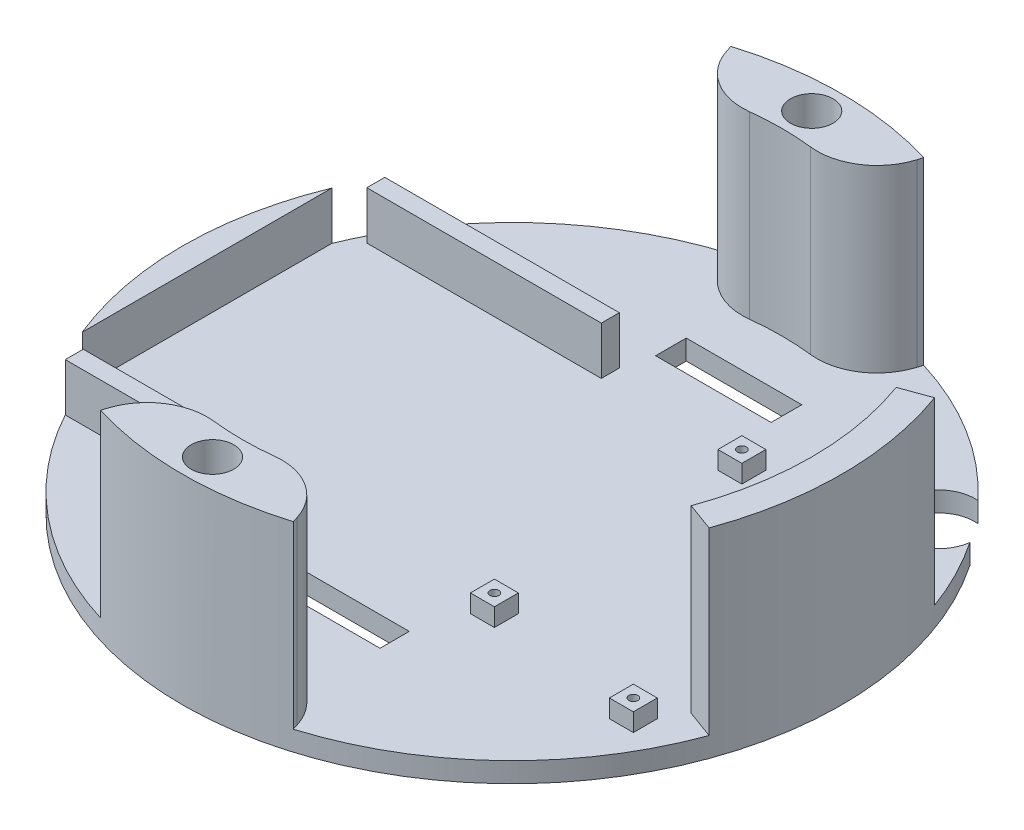
SolidWorks part; units mm, degrees
ref_plane "Front Plane" through (0, 0, 0) normal (0, 0, 1) x (1, 0, 0)
ref_plane "Top Plane" through (0, 0, 0) normal (0, 1, 0) x (1, 0, 0)
ref_plane "Right Plane" through (0, 0, 0) normal (1, 0, 0) x (0, 0, -1)
sketch "Sketch2" plane through (0, 0, 0) normal (0, 1, 0) x (1, 0, 0)
  circle A0 centre (0, 0) radius 69.85
  dimension "D1" = 139.7
extrude "Boss-Extrude1" add sketch "Sketch2" along normal blind 4.2333
sketch "Sketch3" plane through (0, 4.2333, 0) normal (0, 1, 0) x (1, 0, 0)
  line L0 (-20.4222, 66.7979) -> (-16.709, 54.6528)
  line L5 (20.4222, 66.7979) -> (16.709, 54.6528)
  line L6 (16.709, -54.6528) -> (20.4222, -66.7979)
  line L7 (-16.709, -54.6528) -> (-20.4222, -66.7979)
  arc A6 (20.4222, 66.7979) -> (-20.4222, 66.7979) centre (0, 0) ccw
  arc A7 (-16.709, -54.6528) -> (16.709, -54.6528) centre (0, 0) ccw
  arc A8 (-20.4222, -66.7979) -> (20.4222, -66.7979) centre (0, 0) ccw
  arc A9 (16.709, 54.6528) -> (-16.709, 54.6528) centre (0, 0) ccw
  circle M3 centre (0, 0) radius 69.85
  dimension "D1" = 114.3
extrude "Boss-Extrude2" add sketch "Sketch3" along normal blind 38.1 contours A7 L7 L6 M3 | A9 L5 L0 M3
fillet "Fillet3" radius 12.7 1 edges at (-16.709, 23.2833, -54.6528)
fillet "Fillet4" radius 12.7 1 edges at (16.709, 23.2833, 54.6528)
fillet "Fillet5" radius 12.7 1 edges at (-16.709, 23.2833, 54.6528)
sketch "Sketch4" plane through (0, 4.2333, 0) normal (0, 1, 0) x (1, 0, 0)
  line L0 (59.6705, 21.7183) -> (65.6375, 23.8901)
  line L1 (59.6705, -21.7183) -> (65.6375, -23.8901)
  arc A0 (65.6375, -23.8901) -> (65.6375, 23.8901) centre (0, 0) ccw
  arc A1 (59.6705, -21.7183) -> (59.6705, 21.7183) centre (0, 0) ccw
  dimension "D1" = 127
extrude "Boss-Extrude3" add sketch "Sketch4" along normal blind 38.1
sketch "Sketch5" plane through (0, 42.3333, 0) normal (0, 1, 0) x (1, 0, 0)
  circle A0 centre (0, 63.5) radius 4.5085
  circle A1 centre (0, -63.5) radius 4.5085
  arc A3 (-20.4222, -66.7979) -> (20.4222, -66.7979) centre (0, 0) ccw construction
  point P7 (0, -69.85)
  dimension "D1" = 9.017
  dimension "D2" = 9.017
  dimension "D3" = 127
  dimension "D4" = 6.35
extrude "Cut-Extrude1" cut sketch "Sketch5" against normal through all both and the other way through all
fillet "Fillet6" radius 12.7 1 edges at (16.709, 23.2833, -54.6528)
sketch "Sketch6" plane through (0, 4.2333, 0) normal (0, 1, 0) x (1, 0, 0)
  line L7 (-1.2118, 31.378) -> (56.337, 31.378)
  line L8 (-1.2118, 31.378) -> (-1.2118, -30.6716)
  line L9 (-1.2118, -30.6716) -> (56.337, -30.6716)
  line L10 (56.337, 31.378) -> (56.337, -30.6716)
  line L11 (-64.6532, -29.4738) -> (-11.3132, -29.4738)
  line L12 (-64.6532, -29.4738) -> (-64.6532, 30.2162)
  line L13 (-64.6532, 30.2162) -> (-11.3132, 30.2162)
  line L14 (-11.3132, -29.4738) -> (-11.3132, 30.2162)
  dimension "D3" = 62.0497
  dimension "D4" = 57.5488
  dimension "D5" = 59.69
  dimension "D6" = 53.34
sketch "Sketch7" plane through (0, 4.2333, 0) normal (0, 1, 0) x (1, 0, 0)
  line L0 (51.9901, -26.2961) -> (57.0701, -26.2961)
  line L1 (51.9901, -26.2961) -> (51.9901, -31.3761)
  line L2 (51.9901, -31.3761) -> (57.0701, -31.3761)
  line L3 (57.0701, -26.2961) -> (57.0701, -31.3761)
  line L4 (51.9901, -26.2961) -> (57.0701, -31.3761) construction
  line L5 (51.9901, -31.3761) -> (57.0701, -26.2961) construction
  line L7 (17.9901, -21.7461) -> (23.0701, -21.7461)
  line L8 (17.9901, -21.7461) -> (17.9901, -26.8261)
  line L9 (17.9901, -26.8261) -> (23.0701, -26.8261)
  line L10 (23.0701, -21.7461) -> (23.0701, -26.8261)
  line L11 (17.9901, -21.7461) -> (23.0701, -26.8261) construction
  line L12 (17.9901, -26.8261) -> (23.0701, -21.7461) construction
  line L14 (17.8901, 30.8039) -> (22.9701, 30.8039)
  line L15 (17.8901, 30.8039) -> (17.8901, 25.7239)
  line L16 (17.8901, 25.7239) -> (22.9701, 25.7239)
  line L17 (22.9701, 30.8039) -> (22.9701, 25.7239)
  line L18 (17.8901, 30.8039) -> (22.9701, 25.7239) construction
  line L19 (17.8901, 25.7239) -> (22.9701, 30.8039) construction
  line L20 (40.5711, 30.8736) -> (45.7906, 30.8736)
  line L21 (40.5711, 30.8736) -> (40.5711, 25.6542)
  line L22 (40.5711, 25.6542) -> (45.7906, 25.6542)
  line L23 (45.7906, 30.8736) -> (45.7906, 25.6542)
  line L24 (40.5711, 30.8736) -> (45.7906, 25.6542) construction
  line L25 (40.5711, 25.6542) -> (45.7906, 30.8736) construction
  circle A0 centre (54.5301, -28.8361) radius 0.95
  circle A1 centre (20.5301, -24.2861) radius 0.95
  circle A2 centre (20.4301, 28.2639) radius 0.95
  circle A3 centre (43.1809, 28.2639) radius 0.95
  dimension "D1" = 1.9
  dimension "D5" = 0.1
  dimension "D2" = 5.08
  dimension "D3" = 4.55
  dimension "D4" = 34
  dimension "D6" = 52.55
  dimension "D7" = 22.7508
  dimension "D8" = 0
  dimension "D9" = 5.08
  dimension "D10" = 5.08
extrude "Boss-Extrude4" add sketch "Sketch7" along normal blind 3.81
sketch "Sketch8" plane through (0, 4.2333, 0) normal (0, 1, 0) x (1, 0, 0)
  line L0 (-64.6532, 26.4383) -> (-64.6532, -26.4383)
  line L1 (-22.015, -29.4738) -> (-22.015, -33.2838)
  line L2 (-64.6532, -29.4738) -> (-11.3132, -29.4738) construction
  line L3 (-22.015, -33.2838) -> (-61.4102, -33.2838)
  line L4 (-61.4102, -33.2838) -> (-61.4102, -29.4738)
  line L5 (-61.4102, -29.4738) -> (-22.015, -29.4738)
  line L6 (-11.3132, 30.2162) -> (-11.3132, 34.0262)
  line L7 (-11.3132, 34.0262) -> (-61.002, 34.0262)
  line L8 (-61.002, 34.0262) -> (-61.002, 30.2162)
  line L9 (-64.6532, 30.2162) -> (-11.3132, 30.2162) construction
  line L10 (-61.002, 30.2162) -> (-11.3132, 30.2162)
  arc A0 (-64.6532, -26.4383) -> (-64.6532, 26.4383) centre (0, 0) cw
  arc A1 (-20.4222, 66.7979) -> (-20.4222, -66.7979) centre (0, 0) ccw construction
  dimension "D1" = 3.81
  dimension "D2" = 3.81
extrude "Boss-Extrude5" add sketch "Sketch8" along normal blind 10.16
sketch "Sketch9" plane through (0, 8.0433, 0) normal (0, 1, 0) x (1, 0, 0)
  line L1 (-20.0601, -36.5582) -> (14.7572, -36.5582)
  line L2 (-20.0601, -36.5582) -> (-20.0601, -42.7479)
  line L3 (-20.0601, -42.7479) -> (14.7572, -42.7479)
  line L4 (14.7572, -36.5582) -> (14.7572, -42.7479)
  line L5 (-20.0601, -36.5582) -> (14.7572, -42.7479) construction
  line L6 (-20.0601, -42.7479) -> (14.7572, -36.5582) construction
  line L7 (-9.7299, 46.634) -> (14.7572, 46.634)
  line L8 (-9.7299, 46.634) -> (-9.7299, 40.132)
  line L9 (-9.7299, 40.132) -> (14.7572, 40.132)
  line L10 (14.7572, 46.634) -> (14.7572, 40.132)
  circle A0 centre (20.4301, 28.2639) radius 0.95
  circle A1 centre (43.1809, 28.2639) radius 0.95
  circle A2 centre (20.5301, -24.2861) radius 0.95
  circle A3 centre (54.5301, -28.8361) radius 0.95
  circle A4 centre (50.292, 40.132) radius 7.62
  arc A5 (65.6375, -23.8901) -> (65.6375, 23.8901) centre (0, 0) ccw construction
  point P18 (-2.6515, -39.653)
  dimension "D1" = 15.24
  dimension "D2" = 40.132
  dimension "D3" = 50.292
extrude "Cut-Extrude2" cut sketch "Sketch9" against normal through all both
